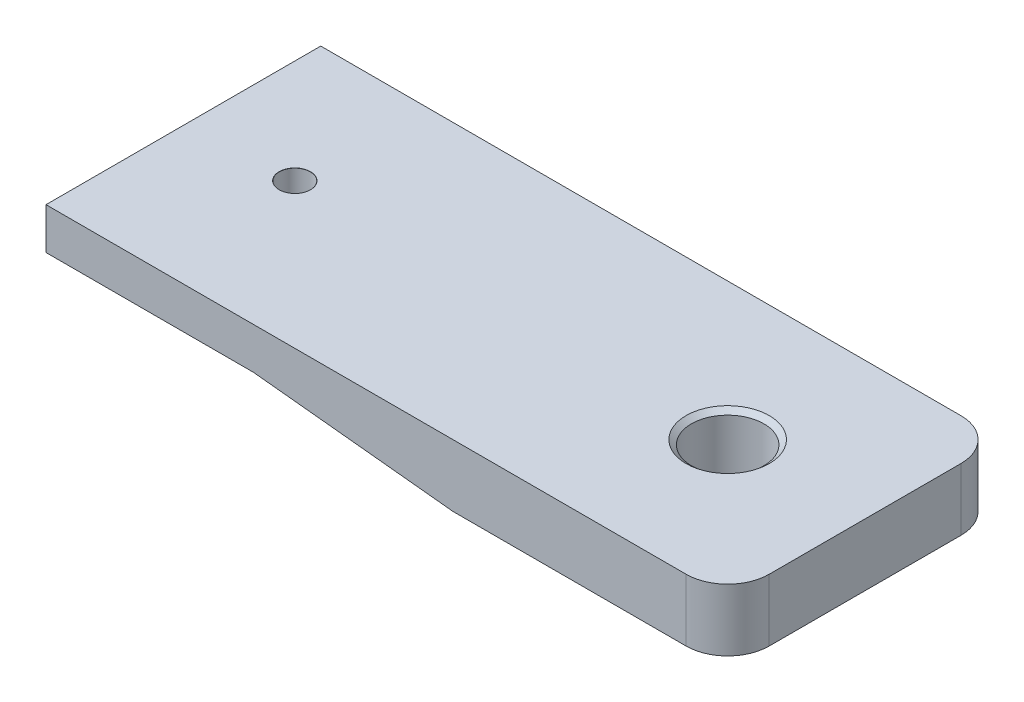
SolidWorks part; units mm, degrees
ref_plane "前视基准面" through (0, 0, 0) normal (0, 0, 1) x (1, 0, 0)
ref_plane "上视基准面" through (0, 0, 0) normal (0, 1, 0) x (1, 0, 0)
ref_plane "右视基准面" through (0, 0, 0) normal (1, 0, 0) x (0, 0, -1)
other "Configuration Table"
sketch "草图2" plane through (0, 0, 0) normal (0, 0, 1) x (1, 0, 0)
  line L0 (0, 0) -> (53, 0)
  line L1 (53, 0) -> (53, 12)
  line L2 (53, 12) -> (-78.5, 12)
  line L3 (-78.5, 12) -> (-78.5, 4)
  line L4 (-78.5, 4) -> (-38.5, 4)
  line L10 (-38.5, 4) -> (0, 0)
extrude "凸台-拉伸1" add sketch "草图2" along normal blind 53
fillet "圆角1" radius 8 1 edges at (53, 6, 0)
hole_wizard "Ø16.0mm 暗销孔1" positions "草图4" profile "草图5" hole size "Ø16.0" standard "GB" end condition through all
sketch "草图4" plane through (0, 12, 0) normal (0, 1, 0) x (1, 0, 0)
  line L0 (53, -9.9367) -> (53, 5.759) construction
  line L3 (45, 0) -> (70.617, 0) construction
  line L5 (53, -53) -> (72.1754, -53) construction
  line L8 (0, -70.159) -> (0, 5.425) construction
  point P33 (26.5, -26.5)
  dimension "D1" = 53
  dimension "D2" = 26.5
  dimension "D3" = 26.5
sketch "草图5" plane through (26.5, 12, 26.5) normal (1, 0, 0) x (0, 0, 1)
  line L0 (0, 0) -> (0, 12)
  line L1 (0, 12) -> (7, 12)
  line L2 (7, 12) -> (7, 0.8601)
  line L3 (7, 0.8601) -> (8.025, 0)
  line L5 (8.025, 0) -> (0, 0)
  line L6 (-7, 0.8601) -> (-8.025, 0) construction
  line L11 (0, -6.35) -> (0, 107.95) construction
  dimension "通孔孔直径" = 14
  dimension "通孔孔深度" = 12
  dimension "近端锥形沉头孔直径" = 16.05
  dimension "近端锥形沉头孔角度" = 100
hole_wizard "Ø6.0mm 暗销孔1" positions "草图6" profile "草图7" hole size "Ø6.0" standard "GB" end condition through all
sketch "草图6" plane through (0, 12, 0) normal (0, 1, 0) x (1, 0, 0)
  line L0 (-66.1704, -25) -> (13.5034, -25) construction
  line L2 (-78.5, -53) -> (-78.5, 0) construction
  point P8 (-58.5, -25)
  dimension "D1" = 20
sketch "草图7" plane through (-58.5, 12, 25) normal (1, 0, 0) x (0, 0, 1)
  line L0 (0, 0) -> (0, 12)
  line L1 (0, 12) -> (3, 12)
  line L2 (3, 12) -> (3, 0.021)
  line L3 (3, 0.021) -> (3.025, 0)
  line L5 (3.025, 0) -> (0, 0)
  line L6 (-3, 0.021) -> (-3.025, 0) construction
  line L11 (0, -6.35) -> (0, 107.95) construction
  dimension "通孔孔直径" = 6
  dimension "通孔孔深度" = 12
  dimension "近端锥形沉头孔直径" = 6.05
  dimension "近端锥形沉头孔角度" = 100
fillet "圆角4" radius 8 1 edges at (53, 6, 53)
